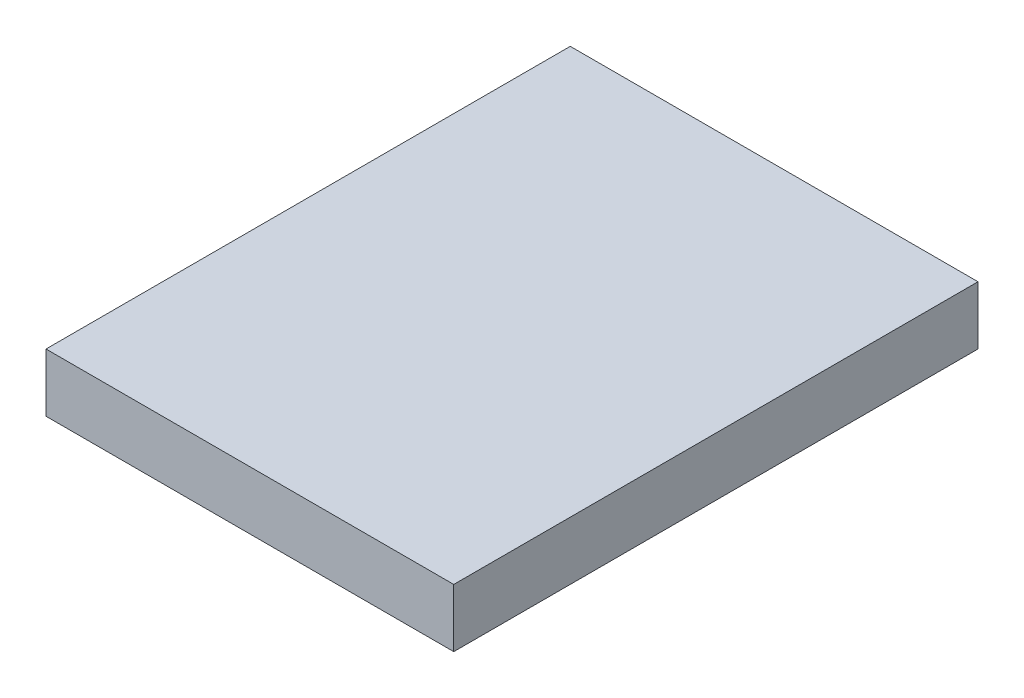
SolidWorks part; units mm, degrees
material "Polyurethane Foam Rigid"
ref_plane "X-Y Datum" through (0, 0, 0) normal (0, 0, 1) x (1, 0, 0)
ref_plane "X-Z Datum" through (0, 0, 0) normal (0, 1, 0) x (1, 0, 0)
ref_plane "Y-Z Datum" through (0, 0, 0) normal (1, 0, 0) x (0, 0, -1)
sketch "Sketch1" plane through (0, 0, 0) normal (0, 0, 1) x (1, 0, 0)
  line L1 (-88.9, -12.7) -> (88.9, -12.7)
  line L2 (-88.9, -12.7) -> (-88.9, 12.7)
  line L3 (-88.9, 12.7) -> (88.9, 12.7)
  line L4 (88.9, -12.7) -> (88.9, 12.7)
  line L5 (-88.9, -12.7) -> (88.9, 12.7) construction
  line L6 (-88.9, 12.7) -> (88.9, -12.7) construction
  point P0 (0, 0)
  dimension "D1" = 25.4
  dimension "D2" = 177.8
extrude "Boss-Extrude1" add sketch "Sketch1" along normal blind 228.6
